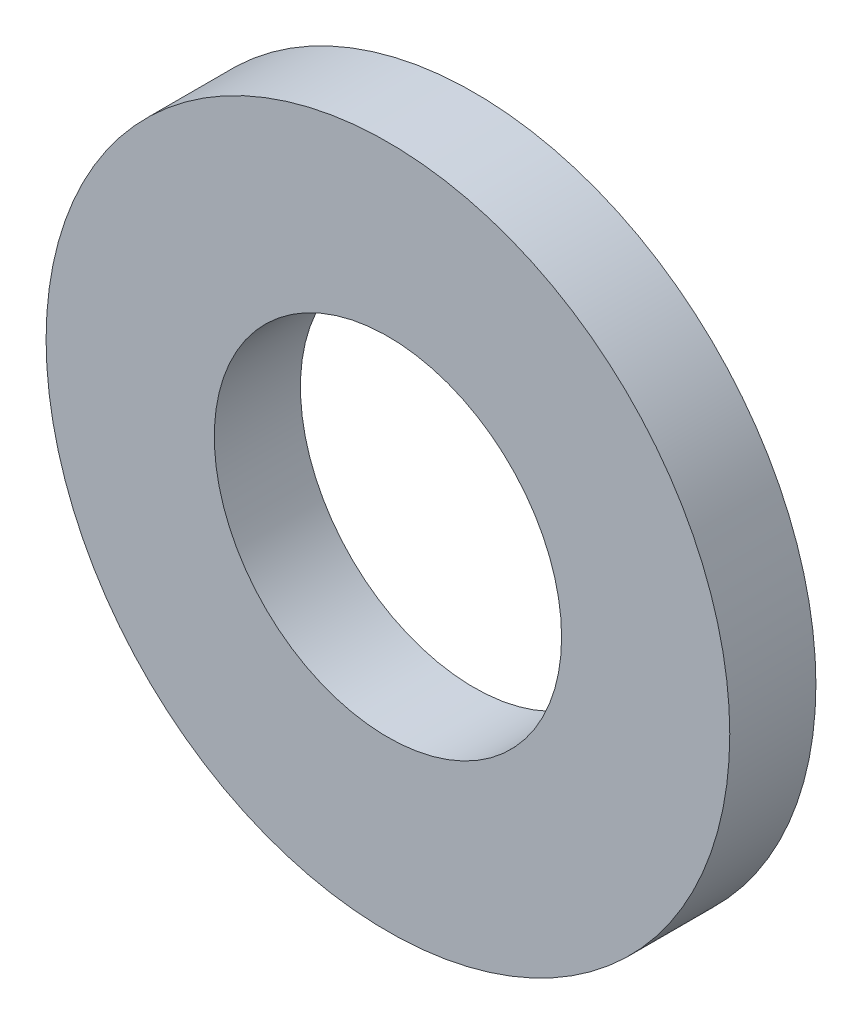
SolidWorks part; units mm, degrees
ref_plane "Front Plane" through (0, 0, 0) normal (0, 0, 1) x (1, 0, 0)
ref_plane "Top Plane" through (0, 0, 0) normal (0, 1, 0) x (1, 0, 0)
ref_plane "Right Plane" through (0, 0, 0) normal (1, 0, 0) x (0, 0, -1)
sketch "Sketch1" plane through (0, 0, 0) normal (0, 0, 1) x (1, 0, 0)
  circle A0 centre (0, 0) radius 6.35
  circle A1 centre (0, 0) radius 3.2258
  dimension "D1" = 12.7
extrude "Boss-Extrude1" add sketch "Sketch1" along normal blind 1.6
